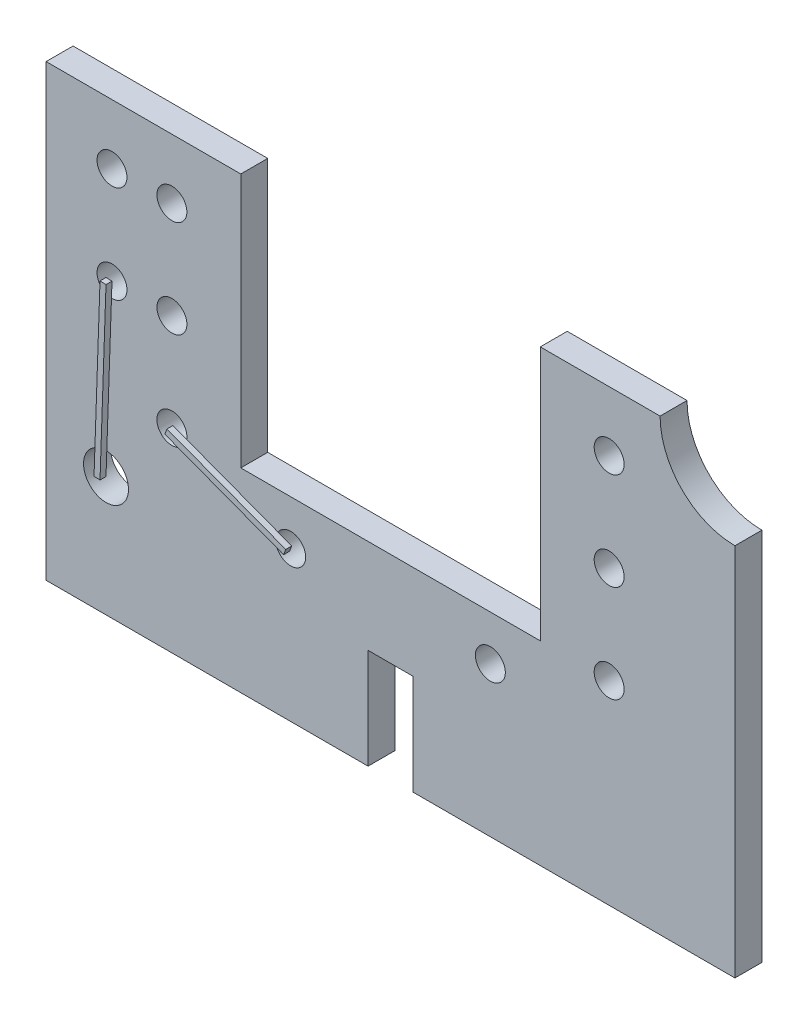
SolidWorks part; units mm, degrees
ref_plane "Спереди" through (0, 0, 0) normal (0, 0, 1) x (1, 0, 0)
ref_plane "Сверху" through (0, 0, 0) normal (0, 1, 0) x (1, 0, 0)
ref_plane "Справа" through (0, 0, 0) normal (1, 0, 0) x (0, 0, -1)
sketch "Эскиз1" plane through (0, 0, 0) normal (0, 0, 1) x (1, 0, 0)
  line L0 (-11.5, -18.5) -> (11.5, -18.5)
  line L1 (-11.5, -18.5) -> (-11.5, -6)
  line L3 (-5, -3.5) -> (-5, -12)
  line L4 (-5, -12) -> (5, -12)
  line L5 (0, 0) -> (0, -18.5) construction
  line L6 (5, -3.5) -> (5, -12)
  line L8 (11.5, -18.5) -> (11.5, -6)
  line L9 (5, -3.5) -> (9, -3.5)
  line L10 (-5, -2) -> (-5, -10.5) construction
  line L11 (-3.5, -12) -> (3.5, -12) construction
  line L12 (-9, -3.5) -> (-11.5, -3.5)
  line L13 (-11.5, -3.5) -> (-11.5, -6)
  line L14 (-5, -3.5) -> (-9, -3.5)
  line L16 (-9, -3.5) -> (-9, -2.3761) construction
  line L18 (-11.5, -6) -> (-13.5487, -6) construction
  arc A0 (-9, -3.5) -> (-11.5, -6) centre (-11.5, -3.5) cw construction
  arc A1 (9, -3.5) -> (11.5, -6) centre (11.5, -3.5) ccw
  point P12 (0, -12)
  point P20 (-14, -3)
  dimension "D1" = 0.5
  dimension "D2" = 4
  dimension "D3" = 23
  dimension "D4" = 15
extrude "Бобышка-Вытянуть1" add sketch "Эскиз1" along normal mid plane 0.9
sketch "Эскиз2" plane through (0, 0, 0) normal (0, 0, 1) x (1, 0, 0)
  line L0 (-11.5, -18.5) -> (11.5, -18.5) construction
  line L1 (-0.75, -15.25) -> (0.75, -15.25) construction
  line L2 (-0.75, -15.25) -> (-0.75, -18.5)
  line L3 (-0.75, -18.5) -> (0.75, -18.5)
  line L4 (0.75, -15.25) -> (0.75, -18.5)
  line L5 (0, -18.5) -> (0, -15.25) construction
  line L6 (-0.75, -15.25) -> (-0.75, -15.15)
  line L11 (-0.75, -15.15) -> (0.75, -15.15)
  line L12 (0, -15.25) -> (0, -12) construction
  line L13 (5, -12) -> (-5, -12) construction
  line L14 (0, -12) -> (0, 0) construction
  line L15 (0.75, -15.15) -> (0.75, -15.25)
  dimension "D1" = 1.5
  dimension "D2" = 0.1
extrude "Вырез-Вытянуть1" cut sketch "Эскиз2" against normal mid plane 10
sketch "Эскиз3" plane through (0, 0, 0) normal (0, 0, 1) x (1, 0, 0)
  line L1 (0, 0) -> (0, -14) construction
  line L2 (7, -3.5) -> (7, -12)
  line L3 (7, -3.5) -> (7, -12) construction
  line L5 (0, -14) -> (7, -14) construction
  line L6 (5, -12) -> (-5, -12) construction
  line L7 (3.5, -14) -> (3.5, -12) construction
  line L8 (-7, -14) -> (-4.6667, -14) construction
  line L9 (-4.6667, -14) -> (-2.3333, -14) construction
  circle A0 centre (7, -5) radius 0.5
  circle A3 centre (7, -8) radius 0.5
  circle A4 centre (7, -11) radius 0.5
  circle A5 centre (7, -14) radius 0.5
  circle A6 centre (-7, -14) radius 0.5
  circle A7 centre (-7, -11) radius 0.5
  circle A8 centre (-7, -8) radius 0.5
  circle A9 centre (-7, -5) radius 0.5
  circle A10 centre (4.6667, -14) radius 0.5
  circle A11 centre (-4.6667, -14) radius 0.5
  circle A13 centre (2.3333, -14) radius 0.5
  circle A14 centre (-2.3333, -14) radius 0.5
  point P10 (7, -4.5)
  dimension "D5" = 1
  dimension "D3" = 1
  dimension "D4" = 2
  dimension "D1" = 2
  dimension "D2" = 4
extrude "Вырез-Вытянуть2" [suppressed] cut sketch "Эскиз3" against normal mid plane 10
sketch "Эскиз6" plane through (0, 0, 0) normal (0, 0, 1) x (1, 0, 0)
  line L0 (5, -12) -> (5, -13.5) construction
  line L1 (-0.75, -15.15) -> (-0.75, -12) construction
  line L2 (5, -12) -> (-5, -12) construction
  line L3 (5, -13.5) -> (3.3333, -13.5) construction
  line L4 (-5, -12) -> (-7.3, -12) construction
  line L5 (-7.3, -12) -> (-7.3, -8.75) construction
  line L6 (-7.3, -8.75) -> (-7.3, -5.5) construction
  line L7 (-7.3, -5.5) -> (-7.3, -3.5) construction
  line L8 (-5, -3.5) -> (-11.5, -3.5) construction
  line L9 (0, -50) -> (0, 50) construction
  line L10 (3.3333, -13.5) -> (1.6667, -13.5) construction
  line L11 (1.6667, -13.5) -> (0, -13.5) construction
  line L12 (0, 0) -> (0, -13.5) construction
  line L13 (3.3333, -13) -> (3.3333, -12) construction
  line L14 (-9.5, -14.5) -> (-9.5, -18.5) construction
  line L15 (-11.5, -18.5) -> (-0.75, -18.5) construction
  line L16 (-9.5, -14.5) -> (-11.5, -14.5) construction
  line L17 (-11.5, -3.5) -> (-11.5, -18.5) construction
  line L18 (-8.8, -8.75) -> (-7.8, -8.75) construction
  line L19 (7.3, -3.5) -> (7.3, -5.5) construction
  line L21 (-5, -3.5) -> (-11.5, -3.5) construction
  line L22 (-6.8, -5.5) -> (-5, -5.5) construction
  line L23 (-5, -12) -> (-5, -3.5) construction
  line L24 (-8.8, -5.5) -> (-7.8, -5.5) construction
  circle A1 centre (3.3333, -13.5) radius 0.5
  circle A2 centre (-7.3, -8.75) radius 0.5
  circle A3 centre (-7.3, -5.5) radius 0.5
  circle A4 centre (7.3, -8.75) radius 0.5
  circle A5 centre (7.3, -5.5) radius 0.5
  circle A6 centre (-3.3333, -13.5) radius 0.5
  circle A7 centre (-7.3, -12) radius 0.5
  circle A8 centre (7.3, -12) radius 0.5
  circle A9 centre (-9.5, -14.5) radius 0.75
  circle A10 centre (-9.3, -8.75) radius 0.5
  circle A11 centre (-9.3, -5.5) radius 0.5
  point P21 (-7.3, -5)
  point P62 (-9.8, -5.5)
  dimension "D1" = 1
  dimension "D3" = 1
  dimension "D6" = 1.5
  dimension "D2" = 1.5
  dimension "D4" = 2
  dimension "D5" = 4
  dimension "D7" = 1
  dimension "D8" = 1.8
extrude "Вырез-Вытянуть4" cut sketch "Эскиз6" against normal mid plane 20.2
sketch "Эскиз7" plane through (0, 0, 0.45) normal (0, 0, 1) x (1, 0, 0)
  line L0 (-7.3, -12) -> (-3.3333, -13.5)
extrude "Вытянуть-Тонкостенный1" add sketch "Эскиз7" along normal blind 0.2 thin thin type mid plane wall 0.2
sketch "Эскиз8" plane through (0, 0, -0.45) normal (0, 0, -1) x (-1, 0, 0)
  line L0 (9.3, -8.75) -> (9.3, -5.5)
extrude "Вытянуть-Тонкостенный2" add sketch "Эскиз8" along normal blind 0.2 thin
sketch "Эскиз9" plane through (0, 0, 0.45) normal (0, 0, 1) x (1, 0, 0)
  line L0 (-9.3, -8.75) -> (-9.5, -14.5)
extrude "Вытянуть-Тонкостенный3" add sketch "Эскиз9" along normal blind 0.2 thin
